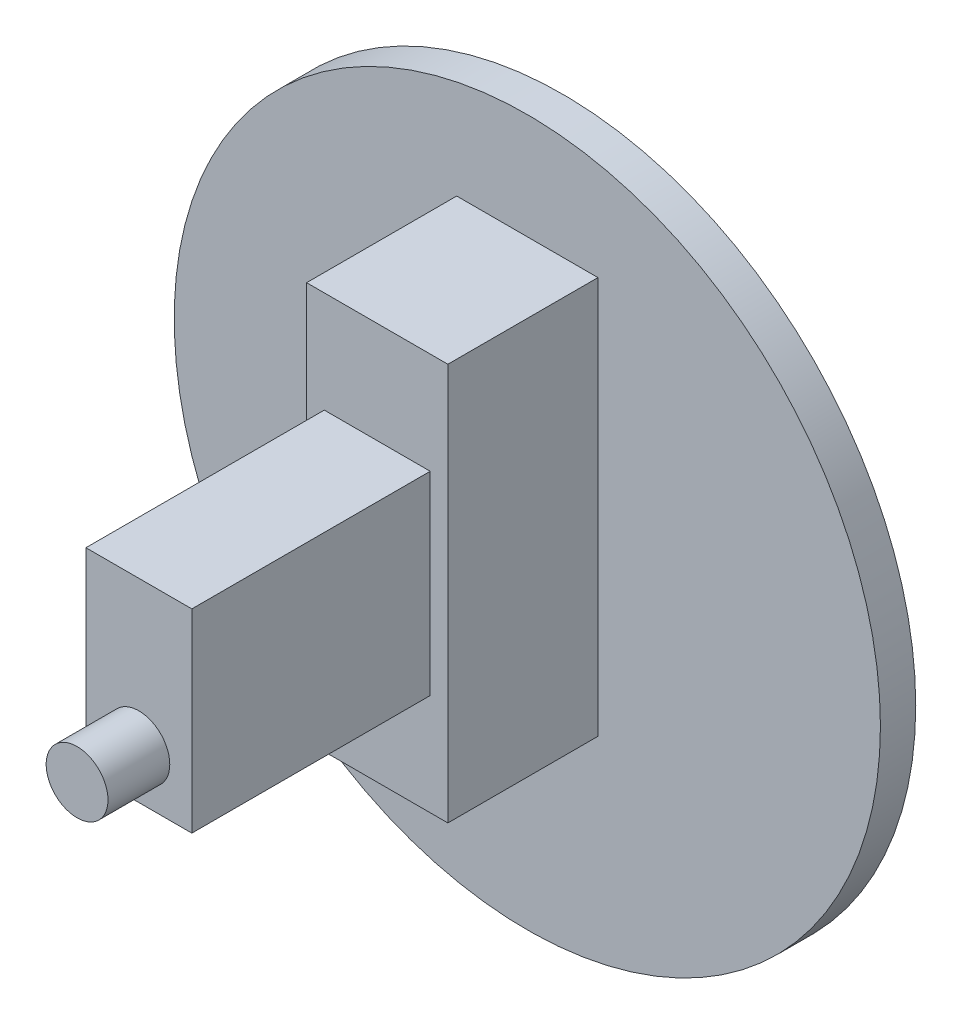
SolidWorks part; units mm, degrees
ref_plane "Ebene vorne" through (0, 0, 0) normal (0, 0, 1) x (1, 0, 0)
ref_plane "Ebene oben" through (0, 0, 0) normal (0, 1, 0) x (1, 0, 0)
ref_plane "Ebene rechts" through (0, 0, 0) normal (1, 0, 0) x (0, 0, -1)
sketch "Skizze1" plane through (0, 0, 0) normal (0, 0, 1) x (1, 0, 0)
  circle A0 centre (0, 0) radius 40
  dimension "D1" = 80
extrude "Aufsatz-Linear austragen1" add sketch "Skizze1" along normal blind 4
sketch "Skizze2" plane through (0, 0, 4) normal (0, 0, 1) x (1, 0, 0)
  line L0 (0, 0) -> (0, 38.9066) construction
  line L1 (-8, 28) -> (8, 28)
  line L2 (-8, 28) -> (-8, -17)
  line L3 (-8, -17) -> (8, -17)
  line L4 (8, 28) -> (8, -17)
  line L5 (0, 0) -> (38.9666, 0) construction
  dimension "D1" = 45
  dimension "D2" = 16
  dimension "D3" = 16
  dimension "D4" = 17
extrude "Aufsatz-Linear austragen2" add sketch "Skizze2" along normal blind 17
sketch "Skizze3" plane through (0, 0, 21) normal (0, 0, 1) x (1, 0, 0)
  line L1 (-6, 16.5) -> (6, 16.5)
  line L2 (-6, 16.5) -> (-6, -5.5)
  line L3 (-6, -5.5) -> (6, -5.5)
  line L4 (6, 16.5) -> (6, -5.5)
  line L6 (8, -17) -> (8, 28) construction
  line L7 (-8, -17) -> (8, -17) construction
  dimension "D1" = 22
  dimension "D2" = 12
  dimension "D3" = 2
  dimension "D4" = 11.5
extrude "Aufsatz-Linear austragen3" add sketch "Skizze3" along normal blind 27 contours L1 L4 L3 L2
sketch "Skizze4" plane through (0, 0, 48) normal (0, 0, 1) x (1, 0, 0)
  circle A0 centre (0, 0) radius 3.5
  dimension "D1" = 7
extrude "Aufsatz-Linear austragen4" add sketch "Skizze4" along normal blind 7
